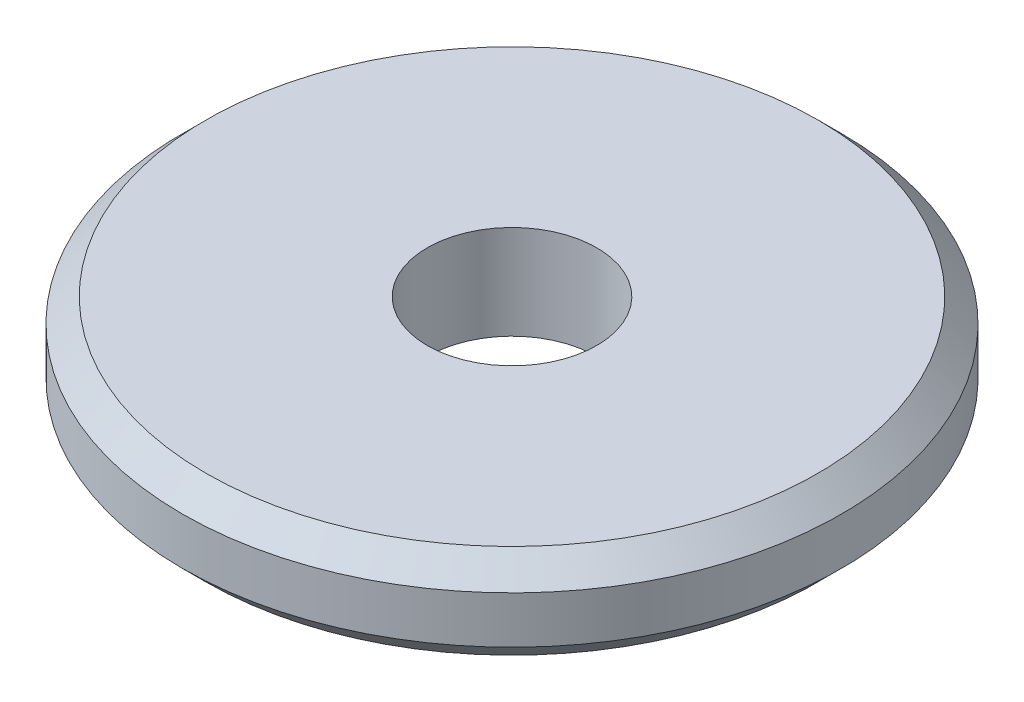
SolidWorks part; units mm, degrees
ref_plane "Front Plane" through (0, 0, 0) normal (0, 0, 1) x (1, 0, 0)
ref_plane "Top Plane" through (0, 0, 0) normal (0, 1, 0) x (1, 0, 0)
ref_plane "Right Plane" through (0, 0, 0) normal (1, 0, 0) x (0, 0, -1)
sketch "Sketch1" plane through (0, 0, 0) normal (0, 1, 0) x (1, 0, 0)
  circle A0 centre (0, 0) radius 7
  circle A1 centre (0, 0) radius 1.8
  dimension "D1" = 14
  dimension "D2" = 3.6
extrude "Boss-Extrude1" add sketch "Sketch1" along normal blind 2
chamfer "Chamfer1" distance 0.5 angle 45 2 edges at (0, 0, 7) (0, 2, 7)
